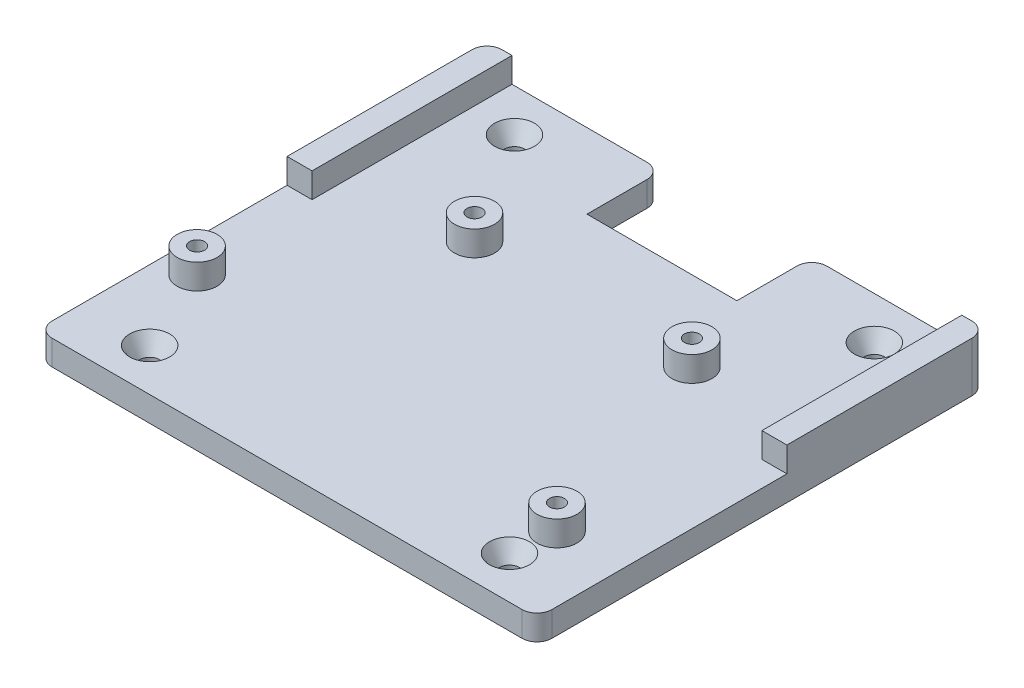
SolidWorks part; units mm, degrees
ref_plane "Alzado" through (0, 0, 0) normal (0, 0, 1) x (1, 0, 0)
ref_plane "Planta" through (0, 0, 0) normal (0, 1, 0) x (1, 0, 0)
ref_plane "Vista lateral" through (0, 0, 0) normal (1, 0, 0) x (0, 0, -1)
sketch "Croquis1" plane through (0, 0, 0) normal (0, 1, 0) x (1, 0, 0)
  line L0 (-36, 36.5) -> (36, -36.5) construction
  line L2 (-50, 45) -> (-50, -45)
  line L3 (-50, -45) -> (50, -45)
  line L4 (50, 45) -> (50, -45)
  line L5 (-50, 45) -> (50, -45) construction
  line L6 (-50, -45) -> (50, 45) construction
  line L7 (-36, -36.5) -> (36, 36.5) construction
  line L8 (-50, 45) -> (-15, 45)
  line L9 (-15, 45) -> (-15, 30)
  line L10 (-15, 30) -> (15, 30)
  line L11 (15, 30) -> (15, 45)
  line L12 (15, 45) -> (50, 45)
  circle A0 centre (-36, -36.5) radius 2
  circle A1 centre (-36, 36.5) radius 2
  circle A2 centre (36, 36.5) radius 2
  circle A3 centre (36, -36.5) radius 2
  point P0 (0, 0)
  point P14 (0, 0)
  point P19 (0, 30)
  dimension "D6" = 4
  dimension "D7" = 30
  dimension "D8" = 15
  dimension "D1" = 100
  dimension "D2" = 90
  dimension "D3" = 73
  dimension "D4" = 72
  dimension "D5" = 73
extrude "Saliente-Extruir2" add sketch "Croquis1" along normal blind 5
chamfer "Chaflán1" distance 2 angle 60 4 edges at (-36, 5, 38.5) (36, 5, 38.5) (36, 5, -34.5) (-36, 5, -34.5)
sketch "Croquis3" plane through (0, 5, 0) normal (0, 1, 0) x (1, 0, 0)
  line L0 (-50, -45) -> (50, -45) construction
  line L1 (-50, 45) -> (-50, -45) construction
  circle A0 centre (-43.5, -19.5) radius 4
  circle A1 centre (37, -28) radius 4
  circle A2 centre (22, 14) radius 4
  circle A3 centre (-21.5, 14) radius 4
  circle A4 centre (-21.5, 14) radius 1.5
  circle A5 centre (-43.5, -19.5) radius 1.5
  circle A6 centre (22, 14) radius 1.5
  circle A7 centre (37, -28) radius 1.5
  dimension "D3" = 8
  dimension "D10" = 3
  dimension "D1" = 25.5
  dimension "D2" = 6.5
  dimension "D4" = 28.5
  dimension "D5" = 59
  dimension "D6" = 87
  dimension "D7" = 17
  dimension "D8" = 72
  dimension "D9" = 59
extrude "Saliente-Extruir3" add sketch "Croquis3" along normal blind 5
sketch "Croquis4" plane through (0, 5, 0) normal (0, 1, 0) x (1, 0, 0)
  line L1 (-50, 45) -> (-45, 45)
  line L2 (-50, 45) -> (-50, 5)
  line L3 (-50, 5) -> (-45, 5)
  line L4 (-45, 45) -> (-45, 5)
  line L5 (50, 45) -> (45, 45)
  line L6 (50, 45) -> (50, 5)
  line L7 (50, 5) -> (45, 5)
  line L8 (45, 45) -> (45, 5)
  point P10 (0, 0)
  point P12 (0, 0)
  dimension "D1" = 5
  dimension "D2" = 5
  dimension "D3" = 40
extrude "Saliente-Extruir4" add sketch "Croquis4" along normal up to surface (5 mm away) up to face at (-21.5, 10, -10)
fillet "Redondeo1" radius 3 6 edges at (50, 2.5, 45) (50, 5, -45) (-50, 5, -45) (-50, 2.5, 45) (-15, 2.5, -45) (15, 2.5, -45)
